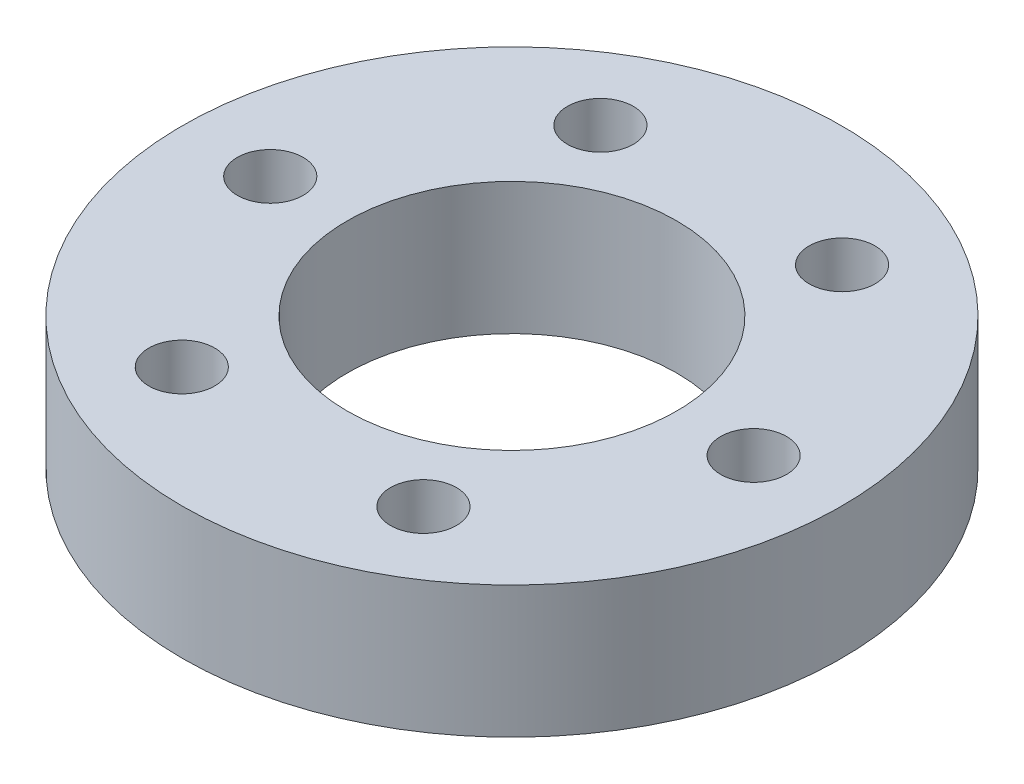
SolidWorks part; units mm, degrees
ref_plane "前视基准面" through (0, 0, 0) normal (0, 0, 1) x (1, 0, 0)
ref_plane "上视基准面" through (0, 0, 0) normal (0, 1, 0) x (1, 0, 0)
ref_plane "右视基准面" through (0, 0, 0) normal (1, 0, 0) x (0, 0, -1)
other "Configuration Table"
sketch "草图1" plane through (0, 0, 0) normal (0, 1, 0) x (1, 0, 0)
  circle A0 centre (0, 0) radius 30
extrude "凸台-拉伸1" add sketch "草图1" along normal blind 12
sketch "草图2" plane through (0, 0, 0) normal (0, 1, 0) x (1, 0, 0)
  circle A0 centre (0, 0) radius 15
extrude "切除-拉伸1" cut sketch "草图2" along normal blind 12
sketch "草图3" plane through (0, 0, 0) normal (0, 1, 0) x (1, 0, 0)
  circle A0 centre (22, 0) radius 3
extrude "切除-拉伸2" cut sketch "草图3" along normal blind 12
pattern_circular "阵列(圆周)1" count 6 over 360 about axis through (0, 0, 0) along (0, 1, 0) of "切除-拉伸2"
